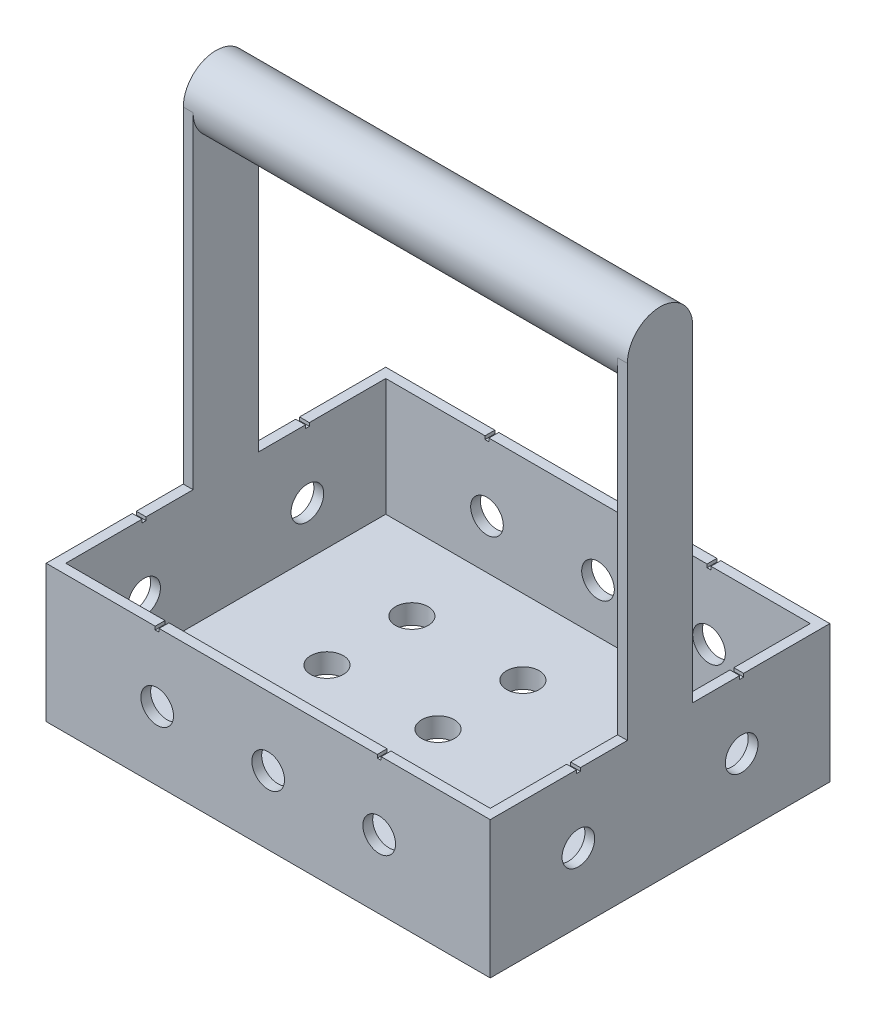
SolidWorks part; units mm, degrees
ref_plane "前视基准面" through (0, 0, 0) normal (0, 0, 1) x (1, 0, 0)
ref_plane "上视基准面" through (0, 0, 0) normal (0, 1, 0) x (1, 0, 0)
ref_plane "右视基准面" through (0, 0, 0) normal (1, 0, 0) x (0, 0, -1)
sketch "草图1" plane through (0, 0, 0) normal (0, 1, 0) x (1, 0, 0)
  line L1 (-68, 52) -> (68, 52)
  line L2 (-68, 52) -> (-68, -52)
  line L3 (-68, -52) -> (68, -52)
  line L4 (68, 52) -> (68, -52)
  line L5 (-68, 52) -> (68, -52) construction
  line L6 (-68, -52) -> (68, 52) construction
  point P0 (0, 0)
  dimension "D1" = 136
  dimension "D2" = 104
extrude "凸台-拉伸1" add sketch "草图1" along normal blind 42
sketch "草图2" plane through (0, 42, 0) normal (0, 1, 0) x (1, 0, 0)
  line L1 (-65, 49) -> (65, 49)
  line L2 (-65, 49) -> (-65, -49)
  line L3 (-65, -49) -> (65, -49)
  line L4 (65, 49) -> (65, -49)
  line L5 (-65, 49) -> (65, -49) construction
  line L6 (-65, -49) -> (65, 49) construction
  point P0 (0, 0)
  dimension "D1" = 130
  dimension "D2" = 98
extrude "切除-拉伸1" cut sketch "草图2" against normal blind 36
sketch "草图3" plane through (0, 6, 0) normal (0, 1, 0) x (1, 0, 0)
  line L0 (-70.8007, 0) -> (69.7878, 0) construction
  line L1 (0, 53.9361) -> (0, -53.3284) construction
  line L2 (-34, 53.9361) -> (-34, -53.3284) construction
  line L3 (34, 53.9361) -> (34, -53.3284) construction
  line L5 (-70.8007, 26) -> (69.7878, 26) construction
  line L6 (-70.8007, -26) -> (69.7878, -26) construction
  circle A0 centre (-34, 26) radius 5
  circle A1 centre (-34, -26) radius 5
  circle A2 centre (34, 26) radius 5
  circle A3 centre (34, -26) radius 5
  circle A4 centre (0, 26) radius 5
  circle A5 centre (0, 0) radius 5
  circle A6 centre (-34, 0) radius 5
  circle A7 centre (0, -26) radius 5
  circle A8 centre (34, 0) radius 5
  dimension "D5" = 10
  dimension "D6" = 10
  dimension "D7" = 10
  dimension "D8" = 10
  dimension "D9" = 10
  dimension "D10" = 10
  dimension "D11" = 10
  dimension "D12" = 10
  dimension "D13" = 10
  dimension "D1" = 34
  dimension "D2" = 34
  dimension "D3" = 26
  dimension "D4" = 26
extrude "切除-拉伸2" cut sketch "草图3" against normal up to next
sketch "草图4" plane through (-68, 0, 0) normal (-1, 0, 0) x (0, 0, 1)
  line L0 (-52, 21) -> (52, 21) construction
  line L1 (-52, 42) -> (-52, 0) construction
  line L2 (52, 42) -> (52, 0) construction
  line L3 (0, 42) -> (0, 0) construction
  line L4 (-52, 42) -> (52, 42) construction
  circle A0 centre (-25, 21) radius 5
  circle A1 centre (25, 21) radius 5
  dimension "D3" = 10
  dimension "D4" = 10
  dimension "D1" = 25
  dimension "D2" = 25
extrude "切除-拉伸3" cut sketch "草图4" against normal blind 136
sketch "草图5" plane through (0, 0, 52) normal (0, 0, 1) x (1, 0, 0)
  line L0 (-68, 21) -> (68, 21) construction
  line L1 (-68, 42) -> (-68, 0) construction
  line L2 (68, 42) -> (68, 0) construction
  line L3 (0, 0) -> (0, 42) construction
  line L4 (-68, 0) -> (68, 0) construction
  line L5 (-68, 42) -> (68, 42) construction
  circle A0 centre (-34, 21) radius 5
  circle A1 centre (34, 21) radius 5
  circle A2 centre (0, 21) radius 5
  dimension "D1" = 10
  dimension "D2" = 10
  dimension "D4" = 34
  dimension "D5" = 10
  dimension "D3" = 34
extrude "切除-拉伸4" cut sketch "草图5" against normal blind 104
sketch "草图6" plane through (0, 42, 0) normal (0, 1, 0) x (1, 0, 0)
  line L0 (-68, 0) -> (68, 0) construction
  line L1 (-68, 52) -> (-68, -52) construction
  line L2 (68, -52) -> (68, 52) construction
  line L3 (0, 52) -> (0, -52) construction
  line L4 (68, 52) -> (-68, 52) construction
  line L5 (-68, -52) -> (68, -52) construction
  line L6 (-65, 49) -> (-65, -49) construction
  line L7 (-68, 10) -> (-65, 10)
  line L8 (-68, 10) -> (-68, -10)
  line L9 (-68, -10) -> (-65, -10)
  line L10 (-65, 10) -> (-65, -10)
  line L12 (68, -10) -> (65, -10)
  line L13 (65, 10) -> (65, -10)
  line L14 (68, 10) -> (65, 10)
  line L15 (68, 10) -> (68, -10)
  dimension "D1" = 20
  dimension "D2" = 10
extrude "凸台-拉伸2" add sketch "草图6" along normal blind 100
sketch "草图7" plane through (-65, 0, 0) normal (1, 0, 0) x (0, 0, -1)
  line L0 (-10, 142) -> (10, 142) construction
  circle A0 centre (0, 142) radius 10
extrude "凸台-拉伸3" add sketch "草图7" along normal blind 130
sketch "草图8" plane through (-68, 0, 0) normal (-1, 0, 0) x (0, 0, 1)
  line L0 (-10, 142) -> (10, 142) construction
  line L1 (-10, 142) -> (10, 142)
  arc A0 (10, 142) -> (-10, 142) centre (0, 142) ccw
extrude "凸台-拉伸4" add sketch "草图8" against normal blind 3
sketch "草图9" plane through (68, 0, 0) normal (1, 0, 0) x (0, 0, -1)
  line L0 (-10, 142) -> (10, 142) construction
  line L1 (-10, 142) -> (10, 142)
  arc A0 (10, 142) -> (-10, 142) centre (0, 142) ccw
extrude "凸台-拉伸5" add sketch "草图9" against normal blind 3
sketch "草图10" plane through (0, 0, 52) normal (0, 0, 1) x (1, 0, 0)
  line L0 (-68, 21) -> (68, 21) construction
  line L1 (-68, 42) -> (-68, 0) construction
  line L2 (68, 42) -> (68, 0) construction
  line L3 (0, 42) -> (0, 0) construction
  line L4 (-68, 42) -> (68, 42) construction
  line L5 (-34, 42) -> (-34, 0) construction
  line L6 (-68, 0) -> (68, 0) construction
  line L7 (34, 42) -> (34, 0) construction
  line L8 (34.6, 41) -> (33.4, 43) construction
  line L9 (-34.6, 43) -> (-33.4, 43)
  line L10 (-34.6, 43) -> (-34.6, 41)
  line L11 (-34.6, 41) -> (-33.4, 41)
  line L12 (-33.4, 43) -> (-33.4, 41)
  line L13 (-34.6, 43) -> (-33.4, 41) construction
  line L14 (-34.6, 41) -> (-33.4, 43) construction
  line L15 (34.6, 43) -> (33.4, 41) construction
  line L16 (33.4, 43) -> (33.4, 41)
  line L17 (34.6, 41) -> (33.4, 41)
  line L18 (34.6, 43) -> (34.6, 41)
  line L19 (34.6, 43) -> (33.4, 43)
  dimension "D1" = 34
  dimension "D2" = 34
  dimension "D3" = 2
  dimension "D4" = 1.2
extrude "切除-拉伸5" cut sketch "草图10" against normal blind 104
sketch "草图11" plane through (-68, 0, 0) normal (-1, 0, 0) x (0, 0, 1)
  line L0 (-52, 21) -> (52, 21) construction
  line L1 (-52, 42) -> (-52, 0) construction
  line L2 (52, 42) -> (52, 0) construction
  line L3 (-25, 42) -> (-25, 0) construction
  line L4 (-52, 42) -> (-10, 42) construction
  line L5 (-52, 0) -> (52, 0) construction
  line L6 (25, 42) -> (25, 0) construction
  line L7 (10, 42) -> (52, 42) construction
  line L8 (0, 0) -> (0, 152) construction
  line L9 (25.6, 41) -> (24.4, 43) construction
  line L10 (-25.6, 43) -> (-24.4, 43)
  line L11 (-25.6, 43) -> (-25.6, 41)
  line L12 (-25.6, 41) -> (-24.4, 41)
  line L13 (-24.4, 43) -> (-24.4, 41)
  line L14 (-25.6, 43) -> (-24.4, 41) construction
  line L15 (-25.6, 41) -> (-24.4, 43) construction
  line L16 (25.6, 43) -> (24.4, 41) construction
  line L17 (24.4, 43) -> (24.4, 41)
  line L18 (25.6, 41) -> (24.4, 41)
  line L19 (25.6, 43) -> (25.6, 41)
  line L20 (25.6, 43) -> (24.4, 43)
  arc A0 (10, 142) -> (-10, 142) centre (0, 142) ccw construction
  dimension "D1" = 25
  dimension "D2" = 25
  dimension "D3" = 2
  dimension "D4" = 1.2
extrude "切除-拉伸6" cut sketch "草图11" against normal blind 136
